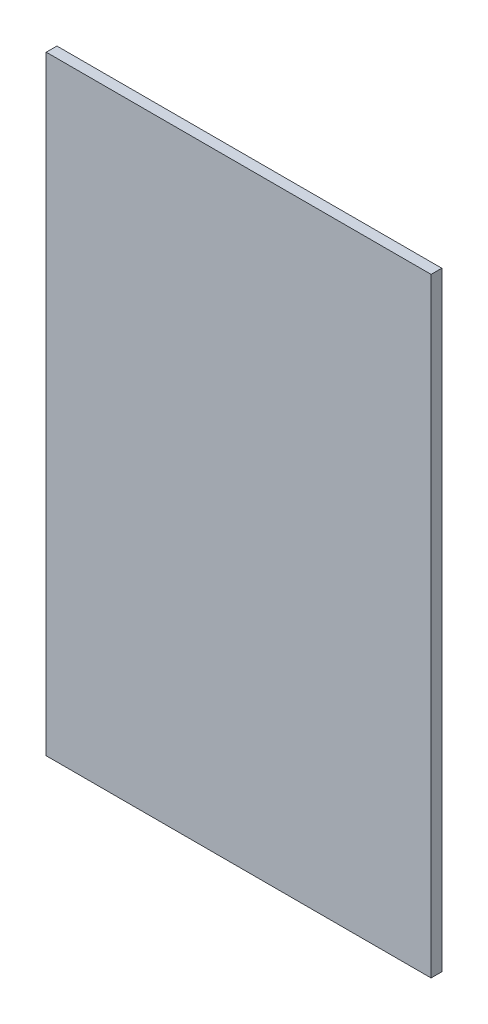
SolidWorks part; units mm, degrees
ref_plane "Front Plane" through (0, 0, 0) normal (0, 0, 1) x (1, 0, 0)
ref_plane "Top Plane" through (0, 0, 0) normal (0, 1, 0) x (1, 0, 0)
ref_plane "Right Plane" through (0, 0, 0) normal (1, 0, 0) x (0, 0, -1)
sketch "Sketch1" plane through (0, 0, 0) normal (0, 0, 1) x (1, 0, 0)
  line L1 (-114.3, -180.975) -> (114.3, -180.975)
  line L2 (-114.3, -180.975) -> (-114.3, 180.975)
  line L3 (-114.3, 180.975) -> (114.3, 180.975)
  line L4 (114.3, -180.975) -> (114.3, 180.975)
  line L5 (-114.3, -180.975) -> (114.3, 180.975) construction
  line L6 (-114.3, 180.975) -> (114.3, -180.975) construction
  point P0 (0, 0)
  dimension "D1" = 361.95
  dimension "D2" = 228.6
extrude "Boss-Extrude1" add sketch "Sketch1" along normal mid plane 6.35
